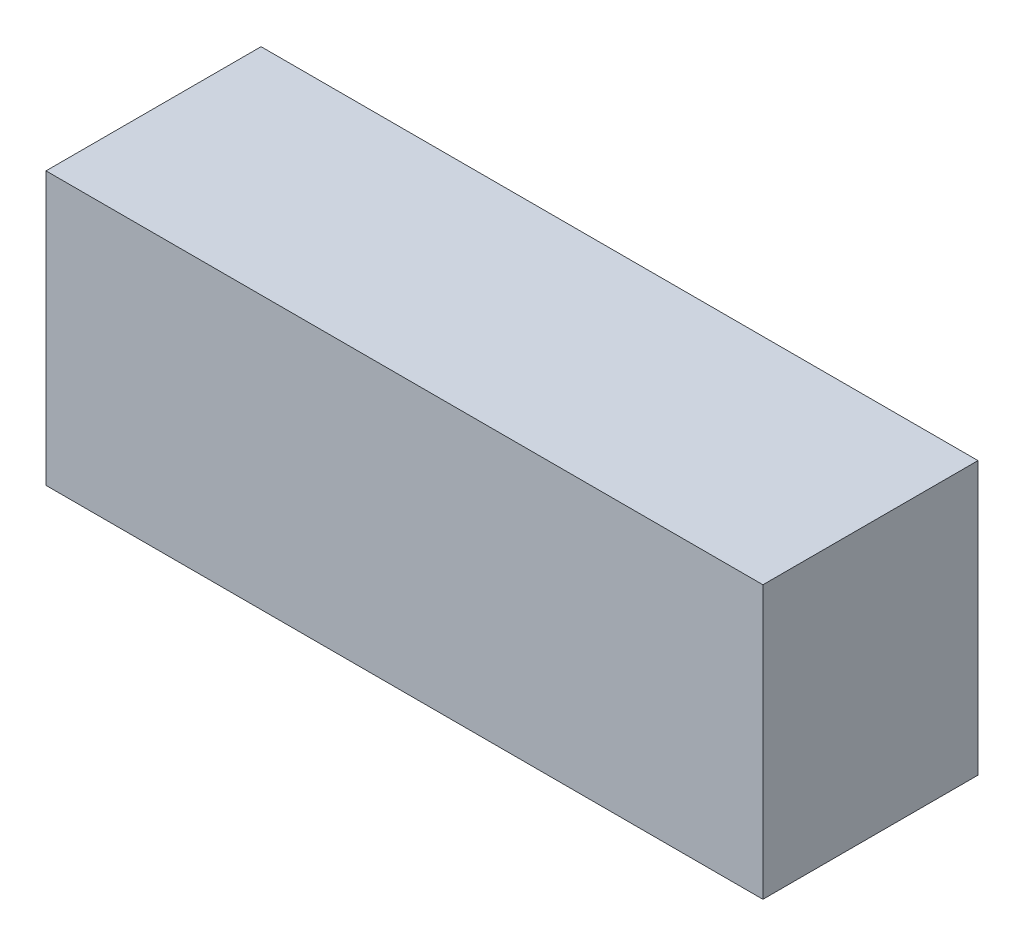
SolidWorks part; units mm, degrees
ref_plane "Front Plane" through (0, 0, 0) normal (0, 0, 1) x (1, 0, 0)
ref_plane "Top Plane" through (0, 0, 0) normal (0, 1, 0) x (1, 0, 0)
ref_plane "Right Plane" through (0, 0, 0) normal (1, 0, 0) x (0, 0, -1)
sketch "Sketch1" plane through (0, 0, 0) normal (0, 1, 0) x (1, 0, 0)
  line L1 (-15.5959, 3.3596) -> (14.4041, 3.3596)
  line L2 (-15.5959, 3.3596) -> (-15.5959, -5.6404)
  line L3 (-15.5959, -5.6404) -> (14.4041, -5.6404)
  line L4 (14.4041, 3.3596) -> (14.4041, -5.6404)
  dimension "D1" = 9
  dimension "D2" = 30
extrude "Boss-Extrude1" add sketch "Sketch1" along normal blind 11.4
